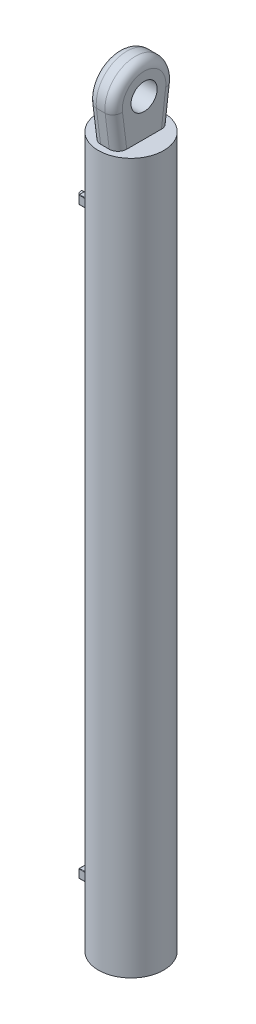
SolidWorks part; units mm, degrees
ref_plane "前视基准面" through (0, 0, 0) normal (0, 0, 1) x (1, 0, 0)
ref_plane "上视基准面" through (0, 0, 0) normal (0, 1, 0) x (1, 0, 0)
ref_plane "右视基准面" through (0, 0, 0) normal (1, 0, 0) x (0, 0, -1)
sketch "草图1" plane through (0, 0, 0) normal (0, 1, 0) x (1, 0, 0)
  circle A0 centre (0, 0) radius 75
  circle A1 centre (0, 0) radius 45
  dimension "D1" = 150
  dimension "D2" = 90
extrude "凸台-拉伸1" add sketch "草图1" along normal blind 1620
sketch "草图2" plane through (0, 1620, 0) normal (0, 1, 0) x (1, 0, 0)
  circle A0 centre (0, 0) radius 75
  circle A1 centre (0, 0) radius 75 construction
extrude "凸台-拉伸2" add sketch "草图2" along normal blind 10
sketch "草图3" plane through (0, 1630, 0) normal (0, 1, 0) x (1, 0, 0)
  line L0 (0, -1000) -> (0, 49000) construction
  line L1 (-1000, 0) -> (49000, 0) construction
  line L2 (-30, 75) -> (30, 75)
  line L3 (-30, 75) -> (-30, -75)
  line L4 (-30, -75) -> (30, -75)
  line L5 (30, 75) -> (30, -75)
  dimension "D1" = 60
  dimension "D2" = 150
extrude "凸台-拉伸3" add sketch "草图3" along normal blind 200
sketch "草图4" plane through (30, 0, 0) normal (1, 0, 0) x (0, 0, -1)
  line L0 (0, 1210) -> (0, 51210) construction
  line L1 (-75, 1830) -> (75, 1830) construction
  line L4 (-68.7386, 1630) -> (68.7386, 1630) construction
  line L5 (75, 1830) -> (75, 1630)
  line L6 (-75, 1830) -> (75, 1830)
  line L7 (75, 1630) -> (60, 1630)
  line L8 (60, 1630) -> (69.4684, 1706.3895)
  line L9 (-75, 1830) -> (-75, 1630)
  line L10 (-75, 1630) -> (-60, 1630)
  line L11 (-60, 1630) -> (-69.4684, 1706.3895)
  arc A0 (-69.4684, 1706.3895) -> (69.4684, 1706.3895) centre (0, 1715) cw
  circle A1 centre (0, 1715) radius 30
  point P5 (0, 1830)
  dimension "D1" = 70
  dimension "D3" = 60
  dimension "D2" = 85
  dimension "D4" = 60
extrude "切除-拉伸1" cut sketch "草图4" against normal through all
fillet "圆角1" radius 20 6 edges at (30, 1668.1947, 64.7342) (30, 1668.1947, -64.7342) (-30, 1668.1947, 64.7342) (-30, 1668.1947, -64.7342) (30, 1785, 0) (-30, 1785, 0)
ref_plane "基准面1" through (0, 100, 0) normal (0, -1, 0) x (-1, 0, 0)
sketch "草图5" plane through (0, 100, 0) normal (0, -1, 0) x (-1, 0, 0)
  line L0 (-1000, 0) -> (49000, 0) construction
  line L1 (75, -1000) -> (75, 49000) construction
  line L3 (73.4847, 15) -> (105, 15)
  line L5 (73.4847, -15) -> (105, -15)
  line L6 (105, 15) -> (105, -15)
  circle A0 centre (0, 0) radius 75 construction
  arc A1 (73.4847, 15) -> (73.4847, -15) centre (0, 0) cw
  dimension "D1" = 30
  dimension "D2" = 30
extrude "凸台-拉伸4" add sketch "草图5" against normal blind 20
sketch "草图6" plane through (0, 120, 0) normal (0, -1, 0) x (-1, 0, 0)
  line L0 (89.2423, -985) -> (89.2423, 49015) construction
  line L1 (105, 15) -> (73.4847, 15) construction
  line L2 (-1105, 0) -> (48895, 0) construction
  line L3 (105, -15) -> (105, 15) construction
  circle A0 centre (89.2423, 0) radius 10
  point P7 (89.2423, 15)
  point P12 (105, 0)
  dimension "D1" = 20
extrude "凸台-拉伸5" add sketch "草图6" against normal blind 660
mirror "镜向2" about plane through (-89.2423, 780, 0) normal (0, -1, 0) of "凸台-拉伸5", "凸台-拉伸4"
sketch "草图10" plane through (-105, 0, 0) normal (-1, 0, 0) x (0, 0, 1)
  line L0 (-1015, 1450) -> (48985, 1450) construction
  line L1 (-15, 1440) -> (-15, 1460) construction
  line L2 (0, 840) -> (0, 50840) construction
  line L3 (15, 1460) -> (-15, 1460) construction
  circle A0 centre (0, 1450) radius 5
  circle A1 centre (0, 1450) radius 2.5
  point P5 (-15, 1450)
  point P10 (0, 1460)
  dimension "D1" = 10
  dimension "D2" = 5
extrude "凸台-拉伸6" add sketch "草图10" along normal blind 10
fillet "圆角2" radius 1 15 edges at (-89.2423, 1440, 15) (-105, 1450, 15) (-89.2423, 1460, 15) (-105, 1440, 0) (-89.2423, 1440, -15) (-105, 1450, -15) (-105, 1460, 0) (-89.2423, 1460, -15) (-89.2423, 100, 15) (-89.2423, 120, 15) (-105, 100, 0) (-89.2423, 100, -15) (-89.2423, 120, -15) (-105, 120, 0) (-105, 110, -15)
